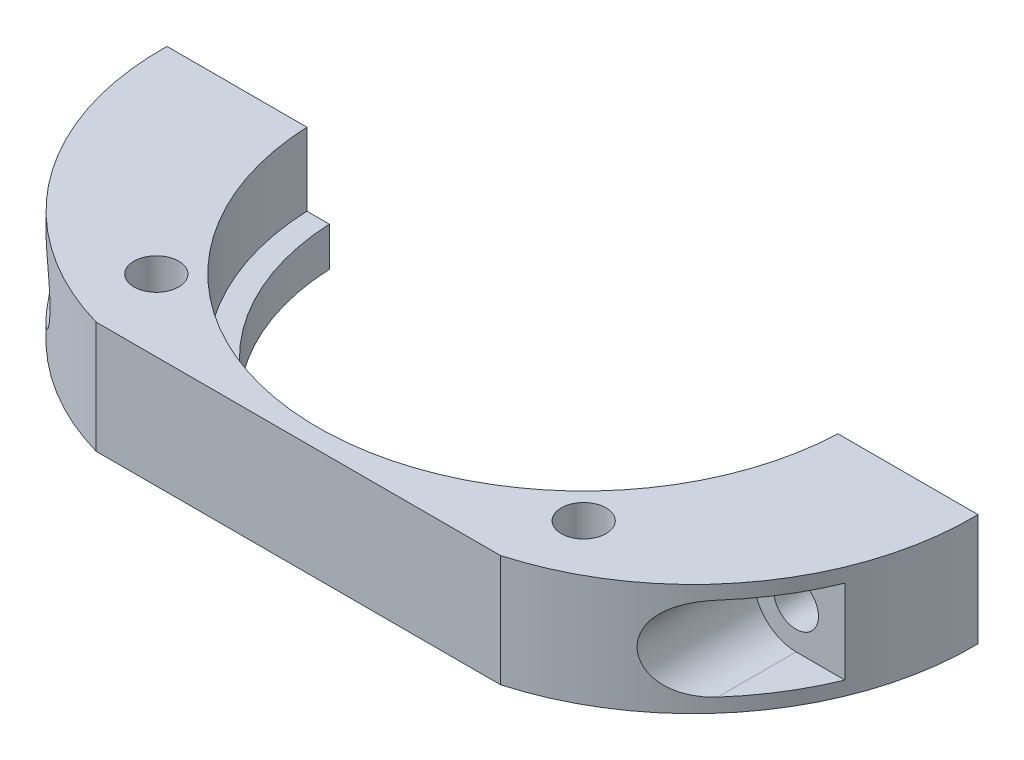
SolidWorks part; units mm, degrees
ref_plane "Front Plane" through (0, 0, 0) normal (0, 0, 1) x (1, 0, 0)
ref_plane "Top Plane" through (0, 0, 0) normal (0, 1, 0) x (1, 0, 0)
ref_plane "Right Plane" through (0, 0, 0) normal (1, 0, 0) x (0, 0, -1)
sketch "Sketch1" plane through (0, 0, 0) normal (0, 1, 0) x (1, 0, 0)
  circle A0 centre (0, 0) radius 62.5
  circle A1 centre (0, 0) radius 43.5
  dimension "D1" = 125
  dimension "D2" = 87
extrude "Boss-Extrude1" add sketch "Sketch1" along normal blind 20
sketch "Sketch2" plane through (0, 20, 0) normal (0, 1, 0) x (1, 0, 0)
  circle A0 centre (0, 0) radius 47.5
  dimension "D1" = 95
extrude "Cut-Extrude1" cut sketch "Sketch2" against normal blind 13
sketch "Sketch3" plane through (0, 20, 0) normal (0, 1, 0) x (1, 0, 0)
  line L0 (0, 0) -> (38.1838, 38.1838) construction
  line L1 (0, 0) -> (54, 0) construction
  circle A0 centre (0, 0) radius 54 construction
  circle A1 centre (38.1838, 38.1838) radius 4
  circle A2 centre (38.1838, -38.1838) radius 4
  circle A3 centre (-38.1838, -38.1838) radius 4
  circle A4 centre (-38.1838, 38.1838) radius 4
  point P14 (0, 0)
  dimension "D1" = 8
  dimension "D3" = 108
  dimension "D4" = 45
  dimension "D2" = 4
extrude "Cut-Extrude2" cut sketch "Sketch3" against normal through all
sketch "Sketch4" plane through (0, 20, 0) normal (0, 1, 0) x (1, 0, 0)
  line L0 (0, 0) -> (0, -2) construction
  line L7 (-75, -2) -> (75, -2)
  line L8 (-75, -2) -> (-75, 62.5)
  line L9 (-75, 62.5) -> (75, 62.5)
  line L10 (75, -2) -> (75, 62.5)
  line L11 (-36.1282, -62.5) -> (36.1282, -62.5)
  line L12 (-36.1282, -62.5) -> (-36.1282, -51)
  line L13 (-36.1282, -51) -> (36.1282, -51)
  line L14 (36.1282, -62.5) -> (36.1282, -51)
  circle A1 centre (0, 0) radius 62.5 construction
  dimension "D1" = 2
  dimension "D2" = 51
  dimension "D3" = 150
extrude "Cut-Extrude3" cut sketch "Sketch4" against normal through all
sketch "Sketch5" plane through (0, 20, 0) normal (0, 1, 0) x (1, 0, 0)
  line L0 (47.4579, -2) -> (62.468, -2) construction
  line L1 (54.9629, -2) -> (84.9629, -2)
  line L2 (54.9629, -2) -> (54.9629, -12)
  line L3 (54.9629, -12) -> (84.9629, -12)
  line L4 (84.9629, -2) -> (84.9629, -12)
  line L5 (-62.468, -2) -> (-47.4579, -2) construction
  line L6 (-54.9629, -2) -> (-84.9629, -2)
  line L7 (-54.9629, -2) -> (-54.9629, -12)
  line L8 (-54.9629, -12) -> (-84.9629, -12)
  line L9 (-84.9629, -2) -> (-84.9629, -12)
  dimension "D1" = 30
  dimension "D2" = 10
extrude "Boss-Extrude2" [suppressed] add sketch "Sketch5" against normal through all
fillet "Fillet1" [suppressed] radius 5
sketch "Sketch6" plane through (0, 20, 0) normal (0, 1, 0) x (1, 0, 0)
  line L0 (-72.468, -2) -> (72.468, -2)
  line L1 (47.4579, -2) -> (62.468, -2) construction
  line L2 (0, 0) -> (0, -2) construction
  line L9 (-47.4579, -2) -> (-62.468, -2)
  line L10 (-36.1282, -51) -> (36.1282, -51)
  line L11 (62.468, -2) -> (47.4579, -2)
  line L12 (-47.4579, -2) -> (-62.468, -2)
  line L13 (-36.1282, -51) -> (36.1282, -51)
  line L14 (62.468, -2) -> (47.4579, -2)
  arc A0 (36.1282, -51) -> (72.468, -2) centre (22.4761, -2.8999) ccw
  arc A1 (-36.1282, -51) -> (-72.468, -2) centre (-22.4761, -2.8999) cw
  arc A8 (-62.468, -2) -> (-36.1282, -51) centre (0, 0) ccw
  arc A9 (36.1282, -51) -> (62.468, -2) centre (0, 0) ccw
  arc A10 (-47.4579, -2) -> (47.4579, -2) centre (0, 0) ccw
  arc A11 (-62.468, -2) -> (-36.1282, -51) centre (0, 0) ccw
  arc A12 (36.1282, -51) -> (62.468, -2) centre (0, 0) ccw
  arc A13 (-47.4579, -2) -> (47.4579, -2) centre (0, 0) ccw
  arc M4 (-62.468, -2) -> (-36.1282, -51) centre (0, 0) ccw
  arc M6 (36.1282, -51) -> (62.468, -2) centre (0, 0) ccw
  dimension "D2" = 50
  dimension "D1" = 10
  dimension "D3" = 0
extrude "Boss-Extrude4" add sketch "Sketch6" against normal through all contours A1 L0 M4 | A0 L0 M6
sketch "Sketch7" plane through (0, 0, 2) normal (0, 0, -1) x (-1, 0, 0)
  line L0 (-72.468, 10) -> (-59.9629, 10) construction
  line L1 (-72.468, 0) -> (-72.468, 20) construction
  line L2 (-59.9629, 10) -> (-59.9629, 20) construction
  line L3 (-47.4579, 20) -> (-72.468, 20) construction
  circle A0 centre (-59.9629, 10) radius 4
  dimension "D1" = 8
extrude "Cut-Extrude4" cut sketch "Sketch7" against normal through all
sketch "Sketch8" plane through (0, 0, 2) normal (0, 0, -1) x (-1, 0, 0)
  line L0 (59.9629, 10) -> (59.9629, 20) construction
  line L1 (72.468, 20) -> (47.4579, 20) construction
  line L2 (59.9629, 10) -> (72.468, 10) construction
  line L3 (72.468, 0) -> (72.468, 20) construction
  circle A0 centre (59.9629, 10) radius 4
  dimension "D1" = 8
extrude "Cut-Extrude5" cut sketch "Sketch8" against normal through all
sketch "Sketch12" plane through (0, 0, 2) normal (0, 0, -1) x (-1, 0, 0)
  line L1 (74.9629, 2.5) -> (59.9629, 2.5)
  line L2 (74.9629, 2.5) -> (74.9629, 17.5)
  line L3 (74.9629, 17.5) -> (59.9629, 17.5)
  line L4 (59.9629, 2.5) -> (59.9629, 17.5) construction
  line L5 (74.9629, 2.5) -> (59.9629, 17.5) construction
  line L6 (74.9629, 17.5) -> (59.9629, 2.5) construction
  line L7 (-59.9629, 10) -> (59.9629, 10) construction
  circle A0 centre (59.9629, 10) radius 7.5
  point P3 (67.4629, 10)
  circle M6 centre (59.9629, 10) radius 4
  line M12 (72.468, 0) -> (72.468, 20)
  dimension "D1" = 15
extrude "Cut-Extrude6" cut sketch "Sketch12" against normal through all from offset 20 contours L2 L3 L1 M12 | A0 M6 | A0 L1 L3 M12 offset against normal yes
mirror "Mirror1" about plane through (0, 0, 0) normal (1, 0, 0) of "Cut-Extrude6"
hole_wizard "M10 Tapped Hole1" positions "3DSketch3" profile "Sketch10" tap size "M10" standard "ISO"
sketch3d "3DSketch3"
  point P6 (-59.9629, 10, 2)
cosmetic thread "Hole Thread1" parameters "D1"=35, "D2"=10
sketch "Sketch10" plane through (-59.9629, 10, 2) normal (1, 0, 0) x (0, 1, 0)
  line L0 (0, 0) -> (0, 42.0537)
  line L1 (0, 42.0537) -> (4.25, 39.5)
  line L2 (4.25, 39.5) -> (4.25, 0.775)
  line L3 (4.25, 0.775) -> (5.025, 0)
  line L5 (5.025, 0) -> (0, 0)
  line L6 (-4.25, 0.775) -> (-5.025, 0) construction
  line L10 (0, 42.0537) -> (-4.25, 39.5) construction
  line L11 (0, -6.35) -> (0, 107.95) construction
  dimension "Tap Drill Dia." = 8.5
  dimension "Tap Drill Depth" = 39.5
  dimension "Near C'Sink Dia." = 10.05
  dimension "Near C'Sink Angle" = 90
  dimension "Drill Angle" = 118
hole_wizard "M10 Tapped Hole2" positions "3DSketch4" profile "Sketch11" tap size "M10" standard "ISO"
sketch3d "3DSketch4"
  line L0 (59.9629, 10, 32.9174) -> (59.9629, 10, 2) construction
  point P0 (59.9629, 10, 2)
sketch "Sketch11" plane through (59.9629, 10, 2) normal (1, 0, 0) x (0, 1, 0)
  line L0 (0, 0) -> (0, 42.0537)
  line L1 (0, 42.0537) -> (4.25, 39.5)
  line L2 (4.25, 39.5) -> (4.25, 0.775)
  line L3 (4.25, 0.775) -> (5.025, 0)
  line L5 (5.025, 0) -> (0, 0)
  line L6 (-4.25, 0.775) -> (-5.025, 0) construction
  line L10 (0, 42.0537) -> (-4.25, 39.5) construction
  line L11 (0, -6.35) -> (0, 107.95) construction
  dimension "Tap Drill Dia." = 8.5
  dimension "Tap Drill Depth" = 39.5
  dimension "Near C'Sink Dia." = 10.05
  dimension "Near C'Sink Angle" = 90
  dimension "Drill Angle" = 118
cosmetic thread "Hole Thread2" parameters "D1"=35, "D2"=10
